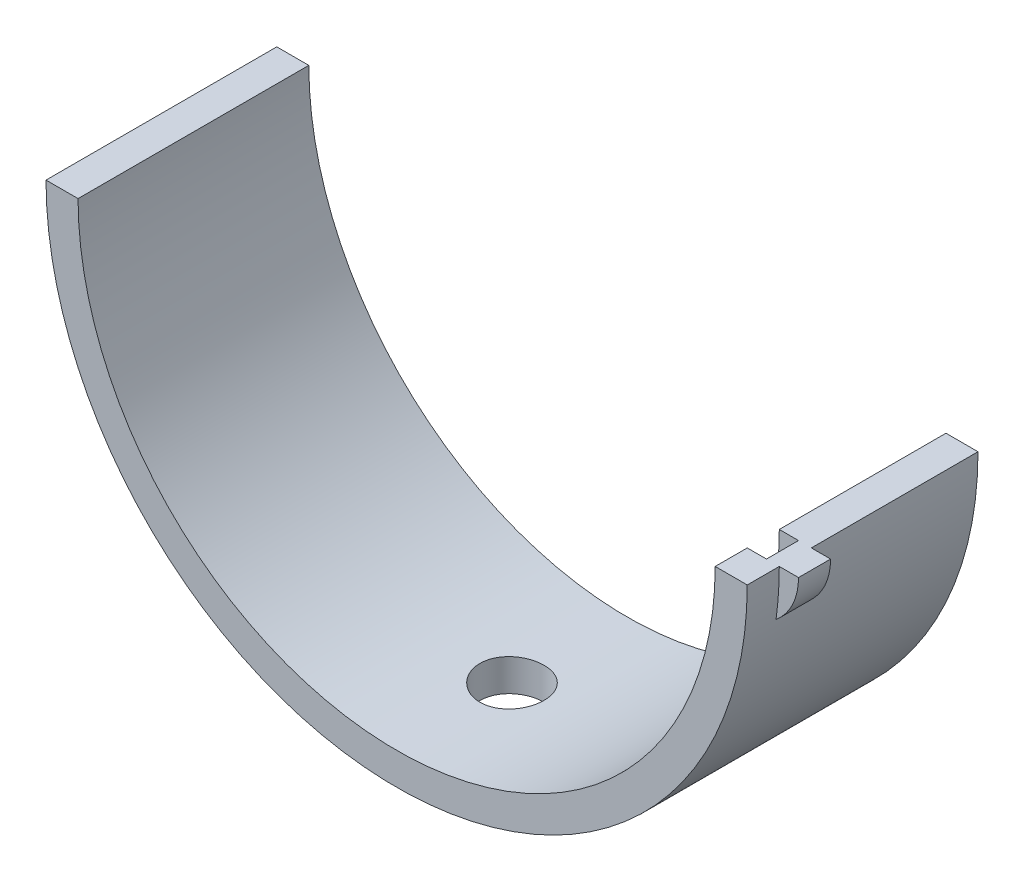
SolidWorks part; units mm, degrees
material "201 Annealed Stainless Steel (SS)"
ref_plane "Front Plane" through (0, 0, 0) normal (0, 0, 1) x (1, 0, 0)
ref_plane "Top Plane" through (0, 0, 0) normal (0, 1, 0) x (1, 0, 0)
ref_plane "Right Plane" through (0, 0, 0) normal (1, 0, 0) x (0, 0, -1)
sketch "Sketch1" plane through (0, 0, 0) normal (0, 0, 1) x (1, 0, 0)
  line L0 (0, 0) -> (-54.6361, 0) construction
  line L1 (-13.8938, 13.8938) -> (13.8938, 13.8938) construction
  line L2 (13.8938, 13.8938) -> (12.6238, 13.8938)
  line L3 (-13.8938, 13.8938) -> (-12.6238, 13.8938)
  circle A0 centre (0, 13.8938) radius 13.8938 construction
  circle A1 centre (0, 13.8938) radius 12.6238 construction
  arc A2 (-12.6238, 13.8938) -> (12.6238, 13.8938) centre (0, 13.8938) ccw
  arc A3 (13.8938, 13.8938) -> (-13.8938, 13.8938) centre (0, 13.8938) cw
  dimension "D1" = 54.6361
  dimension "D2" = 1.27
  dimension "D3" = 25.2476
extrude "Boss-Extrude1" add sketch "Sketch1" against normal blind 9.144
sketch "Sketch2" plane through (0, 0, 0) normal (0, 1, 0) x (1, 0, 0)
  line L0 (13.8938, 0) -> (-13.8938, 9.144) construction
  circle A0 centre (0, 4.572) radius 1.27
  dimension "D1" = 2.54
extrude "Cut-Extrude1" cut sketch "Sketch2" along normal up to next
ref_plane "Plane1" through (0, 0, -1.27) normal (0, 0, 1) x (1, 0, 0)
sketch "Sketch3" plane through (0, 0, -1.27) normal (0, 0, 1) x (1, 0, 0)
  line L0 (12.6238, 13.8938) -> (-12.6238, 13.8938) construction
  line L1 (13.8938, 13.8938) -> (14.6558, 13.8938)
  line L2 (14.6558, 13.8938) -> (14.6558, 15.8611) construction
  arc A0 (13.8938, 13.8938) -> (13.766, 12.0135) centre (0, 13.8938) cw
  arc A1 (13.766, 12.0135) -> (14.6558, 13.8938) centre (12.2242, 13.8938) ccw
  dimension "D1" = 1.9673
  dimension "D2" = 0.762
extrude "Boss-Extrude2" add sketch "Sketch3" against normal blind 1.27
sketch "Sketch4" plane through (0, 0, -1.27) normal (0, 0, 1) x (1, 0, 0)
  line L0 (12.6238, 13.8938) -> (-12.6238, 13.8938) construction
  line L1 (13.3858, 13.8938) -> (12.6238, 13.8938)
  line L2 (13.8938, 13.8938) -> (12.6238, 13.8938) construction
  line L3 (14.6558, 13.8938) -> (13.8938, 13.8938) construction
  line L4 (13.3858, 13.8938) -> (13.3858, 15.3845) construction
  line L5 (13.766, 12.0135) -> (12.483, 12.0135) construction
  arc A0 (12.6238, 13.8938) -> (12.483, 12.0135) centre (0, 13.8938) cw
  arc A1 (13.3858, 13.8938) -> (12.483, 12.0135) centre (10.9763, 13.8938) cw
  arc A2 (-12.6238, 13.8938) -> (12.6238, 13.8938) centre (0, 13.8938) ccw construction
  dimension "D1" = 1.4907
extrude "Cut-Extrude2" cut sketch "Sketch4" against normal blind 1.27
sketch "Sketch5" plane through (0, 13.8938, 0) normal (0, 1, 0) x (1, 0, 0)
  line L0 (0, 4.572) -> (12.6238, 4.572) construction
  line L1 (12.6238, 9.144) -> (12.6238, 2.54) construction
  line L2 (12.5984, 5.842) -> (12.5984, 3.302)
  line L3 (0, 5.842) -> (12.5984, 5.842) construction
  arc A0 (12.5984, 5.842) -> (12.5984, 3.302) centre (11.8618, 4.572) cw
  circle A1 centre (0, 4.572) radius 1.27 construction
  point P8 (12.6238, 5.842)
  dimension "D1" = 0.0254
  dimension "D2" = 0.762
ref_plane "Plane2" through (0, 0, -4.572) normal (0, 0, 1) x (1, 0, 0)
sketch "Sketch6" plane through (0, 0, -4.572) normal (0, 0, 1) x (1, 0, 0)
  line L0 (0, 13.8938) -> (12.6238, 13.8938) construction
  line L1 (13.33, 13.8938) -> (12.5984, 13.8938) construction
  line L2 (0, 13.8938) -> (-12.5984, 13.8938) construction
  arc A0 (12.5984, 13.8938) -> (-12.5984, 13.8938) centre (0, 13.8938) cw
sweep "Cut-Sweep1" [suppressed] cut profiles "Sketch5" path "Sketch6"
